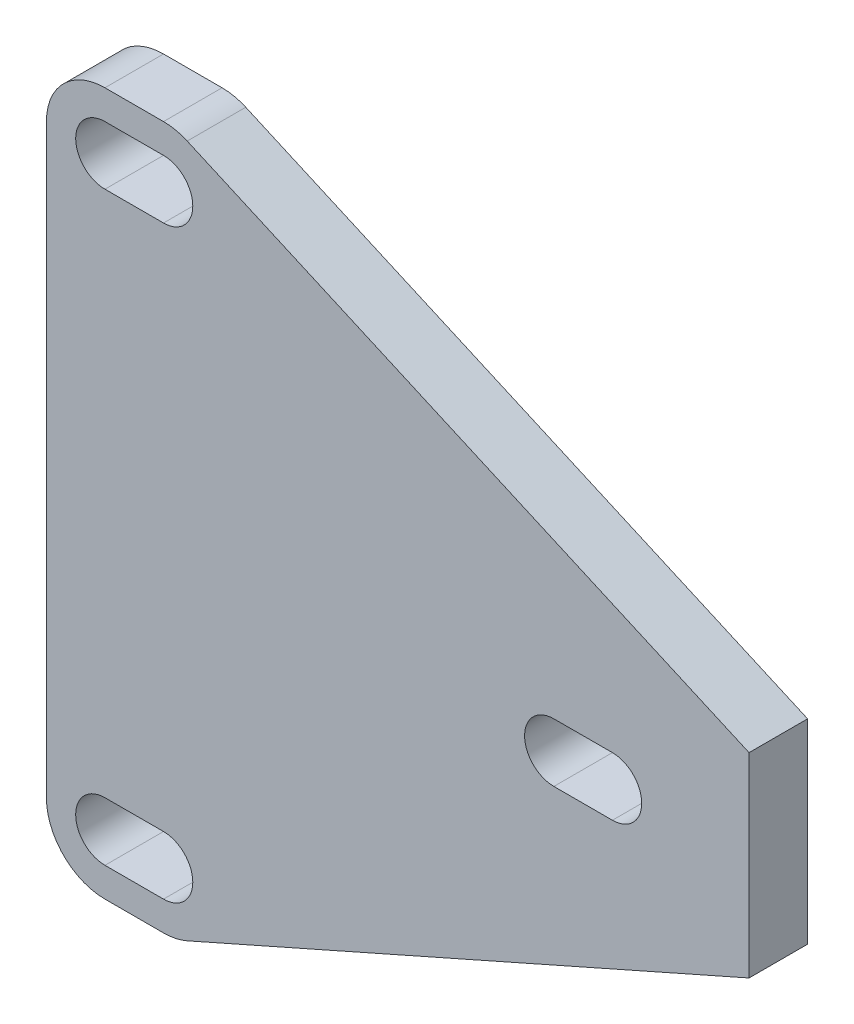
SolidWorks part; units mm, degrees
ref_plane "Front Plane" through (0, 0, 0) normal (0, 0, 1) x (1, 0, 0)
ref_plane "Top Plane" through (0, 0, 0) normal (0, 1, 0) x (1, 0, 0)
ref_plane "Right Plane" through (0, 0, 0) normal (1, 0, 0) x (0, 0, -1)
sketch "Sketch1" plane through (0, 0, 0) normal (0, 0, 1) x (1, 0, 0)
  line L0 (0, 15) -> (0, -15) construction
  line L1 (31.5, 20.9526) -> (31.5, -14.5757) construction
  line L2 (-4.5, 0) -> (31.5, 0) construction
  line L3 (31.5, -5) -> (31.5, 5)
  line L4 (31.5, 5) -> (2.7144, 17.7432)
  line L6 (-4.5, 15) -> (-4.5, -15)
  line L7 (21.5, -1.5) -> (24.5, -1.5)
  line L8 (-1.5, -18) -> (1.5, -18)
  line L9 (-1.5, 16.5) -> (1.5, 16.5)
  line L10 (1.5, 13.5) -> (-1.5, 13.5)
  line L11 (-1.5, 18) -> (1.5, 18)
  line L12 (1.5, -13.5) -> (-1.5, -13.5)
  line L13 (-1.5, -16.5) -> (1.5, -16.5)
  line L14 (21.5, 1.5) -> (24.5, 1.5)
  line L16 (31.5, -5) -> (2.7144, -17.7432)
  circle A0 centre (0, 15) radius 1.5 construction
  arc A1 (-1.5, 18) -> (-4.5, 15) centre (-1.5, 15) ccw
  circle A2 centre (0, -15) radius 1.5 construction
  arc A3 (-1.5, 16.5) -> (-1.5, 13.5) centre (-1.5, 15) ccw
  arc A4 (2.7144, 17.7432) -> (1.5, 18) centre (1.5, 15) ccw
  arc A5 (1.5, 13.5) -> (1.5, 16.5) centre (1.5, 15) ccw
  arc A6 (21.5, 1.5) -> (21.5, -1.5) centre (21.5, 0) ccw
  circle A7 centre (23, 0) radius 1.5 construction
  arc A8 (24.5, -1.5) -> (24.5, 1.5) centre (24.5, 0) ccw
  arc A9 (1.5, -13.5) -> (1.5, -16.5) centre (1.5, -15) cw
  arc A10 (2.7144, -17.7432) -> (1.5, -18) centre (1.5, -15) cw
  arc A11 (-1.5, -16.5) -> (-1.5, -13.5) centre (-1.5, -15) cw
  arc A12 (-1.5, -18) -> (-4.5, -15) centre (-1.5, -15) cw
  point P29 (0, 0)
  dimension "D1" = 3
  dimension "D2" = 6
  dimension "D3" = 31.5
  dimension "D4" = 15
  dimension "D5" = 5
  dimension "D6" = 23
extrude "Boss-Extrude1" add sketch "Sketch1" along normal blind 3
